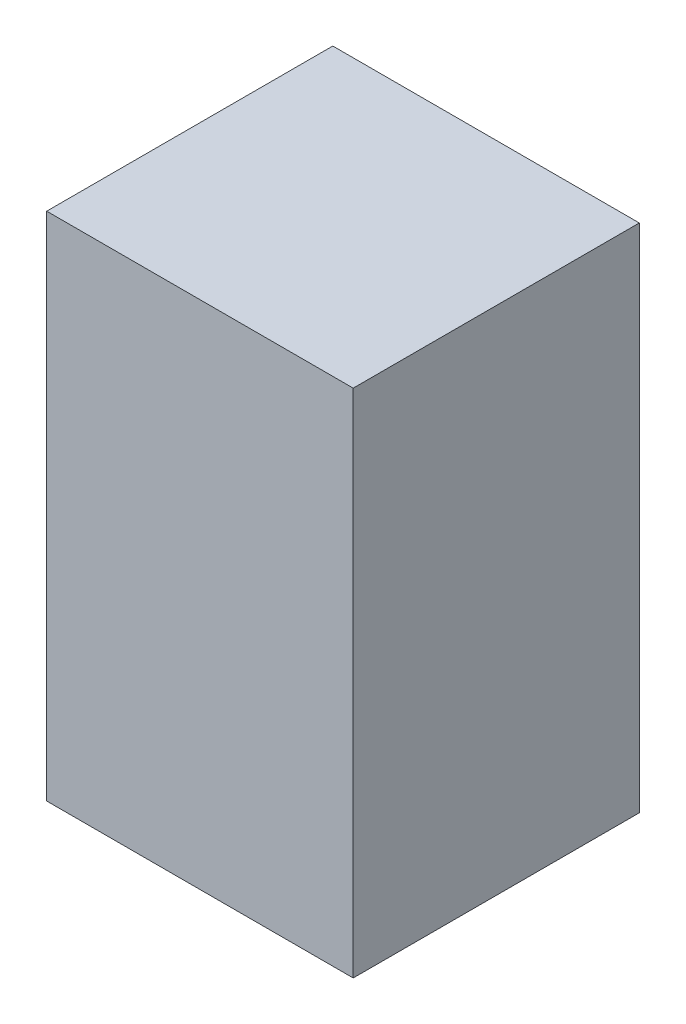
SolidWorks part; units mm, degrees
ref_plane "Alzado" through (0, 0, 0) normal (0, 0, 1) x (1, 0, 0)
ref_plane "Planta" through (0, 0, 0) normal (0, 1, 0) x (1, 0, 0)
ref_plane "Vista lateral" through (0, 0, 0) normal (1, 0, 0) x (0, 0, -1)
sketch "Croquis1" plane through (0, 0, 0) normal (0, 1, 0) x (1, 0, 0)
  line L1 (-22.5, -21) -> (22.5, -21)
  line L2 (-22.5, -21) -> (-22.5, 21)
  line L3 (-22.5, 21) -> (22.5, 21)
  line L4 (22.5, -21) -> (22.5, 21)
  line L5 (-22.5, -21) -> (22.5, 21) construction
  line L6 (-22.5, 21) -> (22.5, -21) construction
  point P0 (0, 0)
  dimension "D1" = 45
  dimension "D2" = 42
extrude "Saliente-Extruir1" add sketch "Croquis1" against normal blind 75
